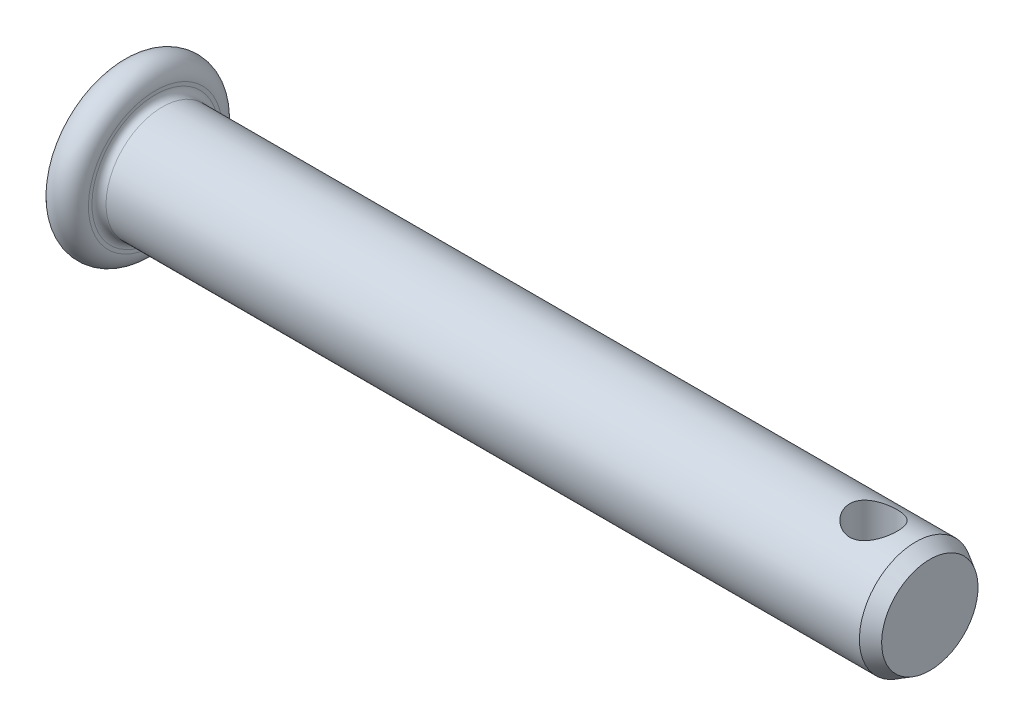
SolidWorks part; units mm, degrees
ref_plane "Front" through (0, 0, 0) normal (0, 0, 1) x (1, 0, 0)
ref_plane "Top" through (0, 0, 0) normal (0, 1, 0) x (1, 0, 0)
ref_plane "Right" through (0, 0, 0) normal (1, 0, 0) x (0, 0, -1)
other "Configuration Table"
sketch "Sketch1" plane through (0, 0, 0) normal (0, 0, 1) x (1, 0, 0)
  line L0 (57.5, 0) -> (0, 0)
  line L1 (0, 0) -> (0, 4.75)
  line L2 (57.5, 0) -> (57.5, 3.4226)
  line L3 (57.5, 3.4226) -> (56.5, 4)
  line L4 (56.5, 4) -> (2.5, 4)
  line L5 (2.5, 4) -> (2.5, 4.75)
  line L6 (-19.83, 0) -> (9.2989, 0) construction
  arc A0 (0, 4.75) -> (2.5, 4.75) centre (1.25, 4.75) cw
  dimension "l" = 55
  dimension "k" = 2.5
  dimension "d" = 8
  dimension "D4" = 30
  dimension "c" = 1
  dimension "dk" = 12
revolve "BaseBody" add sketch "Sketch1" angle 360 about L6
fillet "Chamfer1" radius 0.5 1 edges at (2.5, -4, 0)
sketch "Sketch2" plane through (0, 0, 0) normal (0, 1, 0) x (1, 0, 0)
  line L0 (-19.83, 0) -> (9.2989, 0) construction
  line L1 (57.5, -3.4226) -> (57.5, 3.4226) construction
  circle A0 centre (53.5, 0) radius 1.69
  dimension "D2" = 4
  dimension "d1" = 3.38
extrude "Hole" cut sketch "Sketch2" against normal through all and the other way through all
